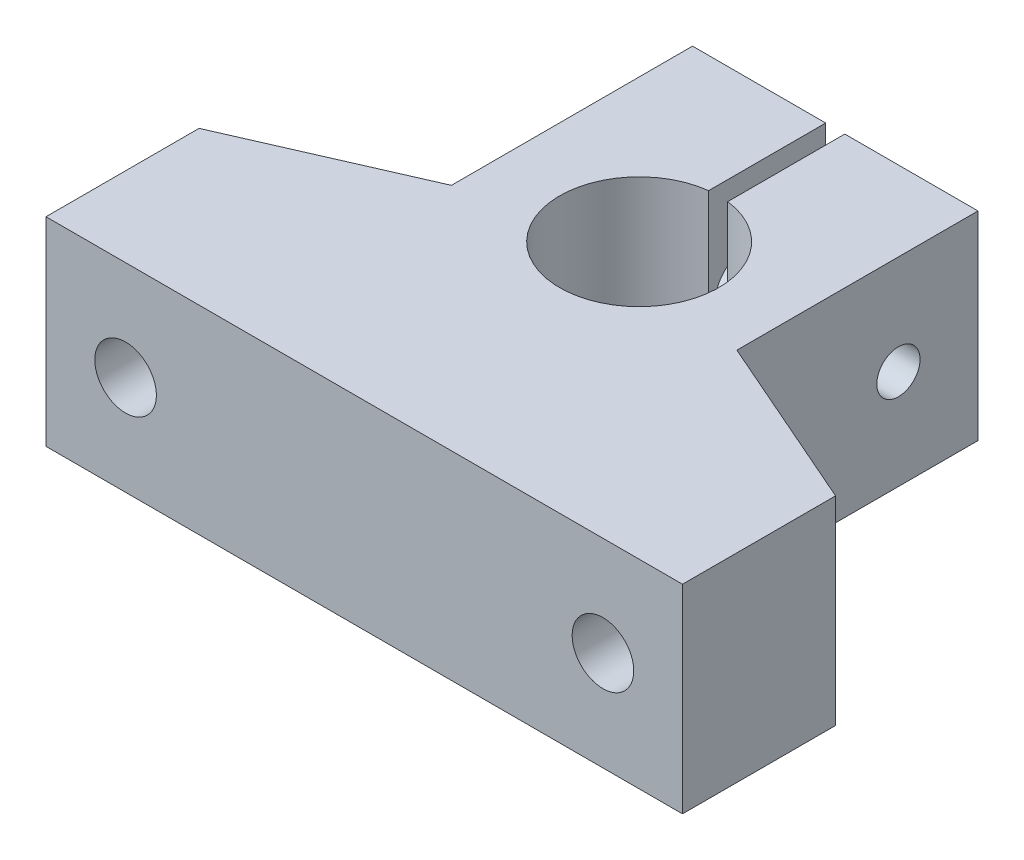
SolidWorks part; units mm, degrees
ref_plane "Front Plane" through (0, 0, 0) normal (0, 0, 1) x (1, 0, 0)
ref_plane "Top Plane" through (0, 0, 0) normal (0, 1, 0) x (1, 0, 0)
ref_plane "Right Plane" through (0, 0, 0) normal (1, 0, 0) x (0, 0, -1)
sketch "Sketch1" plane through (0, 0, 0) normal (0, 1, 0) x (1, 0, 0)
  line L1 (-11.8368, 27.9017) -> (-1.2069, 27.9017)
  line L2 (-11.8368, 27.9017) -> (-11.8368, 8.6574)
  line L3 (0.3171, 27.9017) -> (10.947, 27.9017)
  line L4 (10.947, 27.9017) -> (10.947, 8.6574)
  line L5 (-25.8449, -9.6903) -> (24.9551, -9.6903)
  line L6 (-25.8449, -9.6903) -> (-25.8449, 2.5268)
  line L8 (24.9551, -9.6903) -> (24.9551, 2.5268)
  line L9 (10.947, 8.6574) -> (24.9551, 2.5268)
  line L10 (-1.2069, 27.9017) -> (-1.2069, 18.5545)
  line L11 (-11.8368, 8.6574) -> (-25.8449, 2.5268)
  line L12 (0.3171, 27.9017) -> (0.3171, 18.5545)
  arc A0 (-1.2069, 18.5545) -> (0.3171, 18.5545) centre (-0.4449, 12.2504) ccw
  point P1 (-0.4449, -9.6903)
  dimension "D4" = 6.35
  dimension "D1" = 22.7838
  dimension "D2" = 1.524
  dimension "D5" = 9.3472
  dimension "D6" = 50.8
  dimension "D7" = 37.592
extrude "Boss-Extrude1" add sketch "Sketch1" along normal blind 15.875
hole_wizard "#8-32 Tapped Hole1" positions "Sketch3" profile "Sketch4" tap size "#8-32" standard "ANSI Inch"
sketch "Sketch3" plane through (10.947, 0, 0) normal (1, 0, 0) x (0, 0, -1)
  line L0 (8.6574, 0) -> (27.9017, 0) construction
  line L1 (27.9017, 15.875) -> (27.9017, 0) construction
  point P0 (21.5517, 7.9375)
  dimension "D1" = 7.9375
  dimension "D2" = 6.35
sketch "Sketch4" plane through (10.947, 7.9375, -21.5517) normal (0, 1, 0) x (0, 0, -1)
  line L0 (0, 0) -> (0, 10.6299)
  line L1 (0, 10.6299) -> (1.7272, 10.6299)
  line L2 (1.7272, 10.6299) -> (1.7272, 0)
  line L5 (1.7272, 0) -> (0, 0)
  line L11 (0, -6.35) -> (0, 107.95) construction
  dimension "Thru Tap Drill Dia." = 3.4544
  dimension "Thru Tap Drill Depth" = 10.6299
cosmetic thread "Hole Thread1" parameters "D2"=4.1656
hole_wizard "CBORE for #8 Socket Head Cap Screw1" positions "Sketch6" profile "Sketch5" counterbore size "#8" standard "ANSI Inch"
sketch "Sketch6" plane through (-11.8368, 0, 0) normal (-1, 0, 0) x (0, 0, 1)
  line L0 (-27.9017, 15.875) -> (-27.9017, 0) construction
  line L1 (-27.9017, 0) -> (-8.6574, 0) construction
  point P0 (-21.5517, 7.9375)
  dimension "D1" = 6.35
  dimension "D2" = 7.9375
sketch "Sketch5" plane through (-11.8368, 7.9375, -21.5517) normal (0, 1, 0) x (0, 0, 1)
  line L0 (0, 0) -> (0, 10.6299)
  line L1 (0, 10.6299) -> (2.4574, 10.6299)
  line L3 (2.4574, 10.6299) -> (2.4574, 4.1656)
  line L4 (2.4574, 4.1656) -> (3.9687, 4.1656)
  line L5 (3.9687, 4.1656) -> (3.9687, 0)
  line L7 (3.9687, 0) -> (0, 0)
  line L11 (0, -6.35) -> (0, 107.95) construction
  dimension "Thru Hole Dia." = 4.9149
  dimension "Thru Hole Depth" = 10.6299
  dimension "C'Bore Dia." = 7.9375
  dimension "C'Bore Depth" = 4.1656
ref_plane "Plane1" through (0, 0, -8.6574) normal (0, 0, 1) x (1, 0, 0)
hole_wizard "CBORE for #8 Socket Head Cap Screw2" positions "Sketch8" profile "Sketch7" counterbore size "#8" standard "ANSI Inch" end condition through all
sketch "Sketch8" plane through (0, 0, -8.6574) normal (0, 0, 1) x (1, 0, 0)
  line L0 (24.9551, 0) -> (10.947, 0) construction
  line L1 (-11.8368, 0) -> (-25.8449, 0) construction
  line L2 (24.9551, 15.875) -> (24.9551, 0) construction
  point P0 (18.6051, 7.9375)
  point P2 (-19.4949, 7.9375)
  dimension "D1" = 38.1
  dimension "D2" = 7.9375
  dimension "D3" = 7.9375
  dimension "D4" = 6.35
sketch "Sketch7" plane through (18.6051, 7.9375, -8.6574) normal (1, 0, 0) x (0, 1, 0)
  line L0 (0, 0) -> (0, 18.3477)
  line L1 (0, 18.3477) -> (2.4574, 18.3477)
  line L3 (2.4574, 18.3477) -> (2.4574, 10.5156)
  line L4 (2.4574, 10.5156) -> (3.9687, 10.5156)
  line L5 (3.9687, 10.5156) -> (3.9687, 0)
  line L7 (3.9687, 0) -> (0, 0)
  line L11 (0, -6.35) -> (0, 107.95) construction
  dimension "Thru Hole Dia." = 4.9149
  dimension "Thru Hole Depth" = 18.3477
  dimension "C'Bore Dia." = 7.9375
  dimension "C'Bore Depth" = 10.5156
